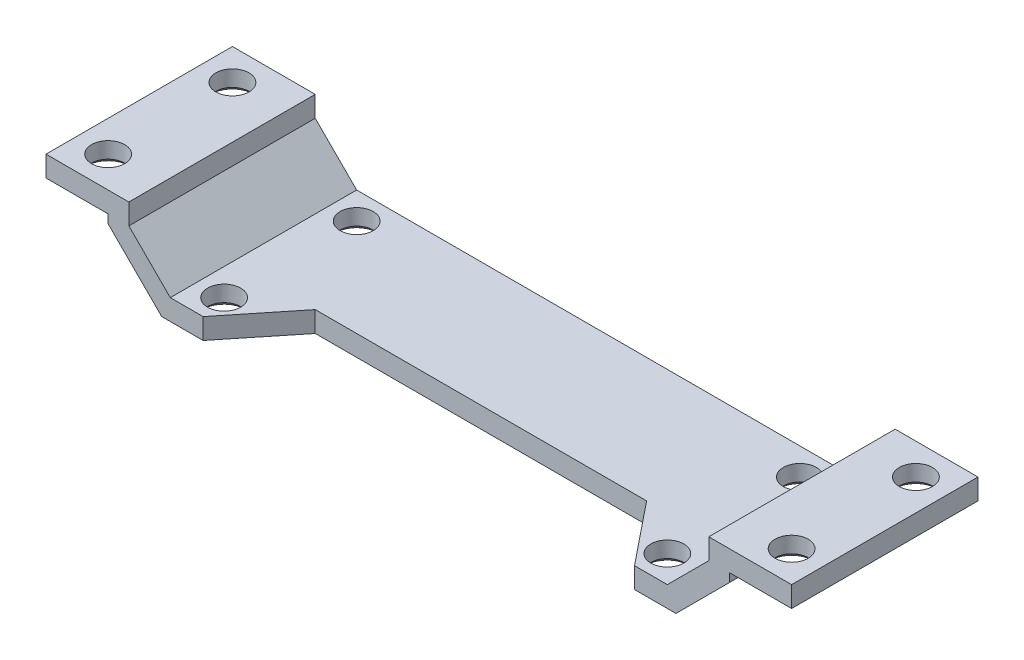
SolidWorks part; units mm, degrees
material "镁合金"
ref_plane "前视基准面" through (0, 0, 0) normal (0, 0, 1) x (1, 0, 0)
ref_plane "上视基准面" through (0, 0, 0) normal (0, 1, 0) x (1, 0, 0)
ref_plane "右视基准面" through (0, 0, 0) normal (1, 0, 0) x (0, 0, -1)
sketch "草图1" plane through (0, 0, 0) normal (0, 0, 1) x (1, 0, 0)
  line L0 (-12, 0) -> (12, 0)
  line L1 (12, 0) -> (14, 2)
  line L2 (14, 2) -> (14, 3)
  line L3 (14, 3) -> (18, 3)
  line L4 (-12, 0) -> (-14, 2)
  line L5 (-14, 2) -> (-14, 3)
  line L6 (-14, 3) -> (-18, 3)
  line L7 (-15, 2) -> (-18, 2)
  line L8 (-15, 1.5858) -> (-15, 2)
  line L9 (-12.4142, -1) -> (-15, 1.5858)
  line L10 (-12.4142, -1) -> (12.4142, -1)
  line L11 (12.4142, -1) -> (15, 1.5858)
  line L12 (15, 1.5858) -> (15, 2)
  line L13 (15, 2) -> (18, 2)
  line L14 (-18, 3) -> (-18, 2)
  line L15 (18, 2) -> (18, 3)
  dimension "D1" = 24
  dimension "D2" = 4
  dimension "D3" = 4
  dimension "D4" = 2
  dimension "D5" = 2
  dimension "D6" = 1
  dimension "D7" = 1
  dimension "D8" = 2
  dimension "D9" = 2
  dimension "D10" = 1
extrude "凸台-拉伸1" add sketch "草图1" along normal blind 9
sketch "草图2" plane through (0, -1, 0) normal (0, -1, 0) x (1, 0, 0)
  line L0 (-10.4142, 9) -> (-8, 6)
  line L1 (-12.4142, 9) -> (12.4142, 9) construction
  line L2 (-8, 6) -> (8, 6)
  line L3 (8, 6) -> (10.4142, 9)
  line L5 (10.4142, 9) -> (-10.4142, 9)
  line L7 (12.4142, 9) -> (12.4142, 0) construction
  point P11 (0, 6)
  dimension "D1" = 2
  dimension "D2" = 16
  dimension "D3" = 2
  dimension "D4" = 3
extrude "切除-拉伸1" cut sketch "草图2" against normal through all
sketch "草图3" plane through (0, 3, 0) normal (0, 1, 0) x (1, 0, 0)
  line L0 (-18, -9) -> (-18, 0) construction
  line L1 (-16.5, -1.5) -> (16.5, -1.5)
  line L2 (-16.5, -1.5) -> (-16.5, -7.5)
  line L3 (-16.5, -7.5) -> (16.5, -7.5)
  line L4 (16.5, -1.5) -> (16.5, -7.5)
  line L5 (-14, 0) -> (-18, 0) construction
  line L6 (-14, -9) -> (-18, -9) construction
  line L7 (18, -9) -> (18, 0) construction
  dimension "D1" = 1.5
  dimension "D2" = 1.5
  dimension "D3" = 1.5
  dimension "D4" = 1.5
hole_wizard "M2 螺纹孔2" positions "草图6" profile "草图7" tap size "M2" standard "GB" end condition up to next
sketch "草图6" plane through (0, 2, 0) normal (0, -1, 0) x (-1, 0, 0)
  point P0 (16.5, -7.5)
  point P3 (16.5, -1.5)
  point P6 (-16.5, -7.5)
  point P9 (-16.5, -1.5)
sketch "草图7" plane through (-16.5, 2, 7.5) normal (1, 0, 0) x (0, 0, -1)
  line L0 (0, 0) -> (0, 1)
  line L1 (0, 1) -> (0.8, 1)
  line L2 (0.8, 1) -> (0.8, 0.225)
  line L3 (0.8, 0.225) -> (1.025, 0)
  line L5 (1.025, 0) -> (0, 0)
  line L6 (-0.8, 0.225) -> (-1.025, 0) construction
  line L11 (0, -6.35) -> (0, 107.95) construction
  dimension "通孔螺纹孔钻头直径" = 1.6
  dimension "通孔螺纹孔钻头深度" = 1
  dimension "近端锥形沉头孔直径" = 2.05
  dimension "近端锥形沉头孔角度" = 90
cosmetic thread "孔螺蚊线2" parameters "D2"=2
cosmetic thread "孔螺蚊线3" parameters "D2"=2
cosmetic thread "孔螺蚊线4" parameters "D2"=2
cosmetic thread "孔螺蚊线5" parameters "D2"=2
sketch "草图8" plane through (0, -1, 0) normal (0, -1, 0) x (1, 0, 0)
  line L1 (-10.7, 7.7) -> (10.7, 7.7)
  line L2 (-10.7, 7.7) -> (-10.7, 1.3)
  line L3 (-10.7, 1.3) -> (10.7, 1.3)
  line L4 (10.7, 7.7) -> (10.7, 1.3)
  line L5 (-12.4142, 9) -> (-10.4142, 9) construction
  line L7 (0, 7.7) -> (0, 1.3) construction
  point P7 (-11.4142, 9)
  dimension "D1" = 6.4
  dimension "D2" = 21.4
  dimension "D3" = 1.3
hole_wizard "M2 螺纹孔3" positions "草图9" profile "草图10" tap size "M2" standard "GB" end condition up to next
sketch "草图9" plane through (0, -1, 0) normal (0, -1, 0) x (-1, 0, 0)
  point P0 (10.7, -7.7)
  point P3 (10.7, -1.3)
  point P6 (-10.7, -1.3)
  point P9 (-10.7, -7.7)
sketch "草图10" plane through (-10.7, -1, 7.7) normal (1, 0, 0) x (0, 0, -1)
  line L0 (0, 0) -> (0, 1)
  line L1 (0, 1) -> (0.8, 1)
  line L2 (0.8, 1) -> (0.8, 0.225)
  line L3 (0.8, 0.225) -> (1.025, 0)
  line L5 (1.025, 0) -> (0, 0)
  line L6 (-0.8, 0.225) -> (-1.025, 0) construction
  line L11 (0, -6.35) -> (0, 107.95) construction
  dimension "通孔螺纹孔钻头直径" = 1.6
  dimension "通孔螺纹孔钻头深度" = 1
  dimension "近端锥形沉头孔直径" = 2.05
  dimension "近端锥形沉头孔角度" = 90
cosmetic thread "孔螺蚊线6" parameters "D2"=2
cosmetic thread "孔螺蚊线7" parameters "D2"=2
cosmetic thread "孔螺蚊线8" parameters "D2"=2
cosmetic thread "孔螺蚊线9" parameters "D2"=2
